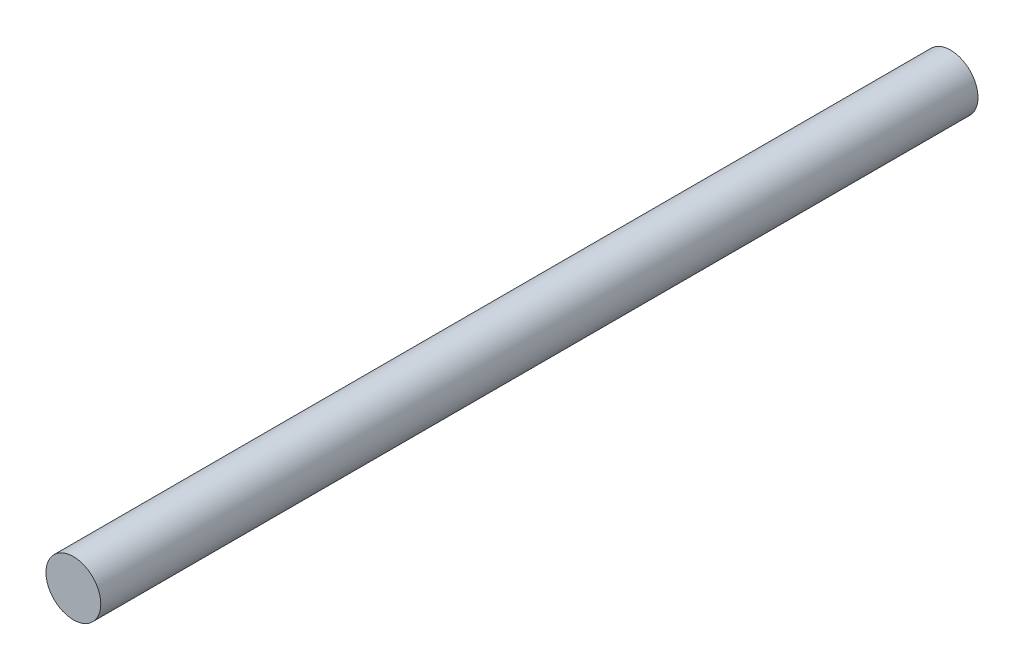
SolidWorks part; units mm, degrees
ref_plane "Front Plane" through (0, 0, 0) normal (0, 0, 1) x (1, 0, 0)
ref_plane "Top Plane" through (0, 0, 0) normal (0, 1, 0) x (1, 0, 0)
ref_plane "Right Plane" through (0, 0, 0) normal (1, 0, 0) x (0, 0, -1)
sketch "Sketch1" plane through (0, 0, 0) normal (0, 0, 1) x (1, 0, 0)
  line L1 (-4.7625, 0) -> (4.7625, 0) construction
  dimension "OD" = 9.525
sketch "Sketch2" plane through (0, 0, 0) normal (1, 0, 0) x (0, 0, -1)
  line L0 (76.2, 0) -> (-76.2, 0)
  point P0 (-63.5, 0)
  point P3 (63.5, 0)
  point P4 (0, 0)
  dimension "Length" = 152.4
  dimension "D1" = 12.7
  dimension "D2" = 12.7
sketch "Sketch3" plane through (0, 0, 0) normal (0, 0, 1) x (1, 0, 0)
  circle A0 centre (0, 0) radius 4.7625
extrude "Boss-Extrude1" add sketch "Sketch3" along normal up to vertex (76.2 mm away) and the other way up to vertex (76.2 mm away) up to point (0, 0, 76.2) other way up to point (0, 0, -76.2)
equation "\"D1@Sketch2\"=\"Length@Sketch2\"/12"
equation "\"D2@Sketch2\"=\"Length@Sketch2\"/12"
